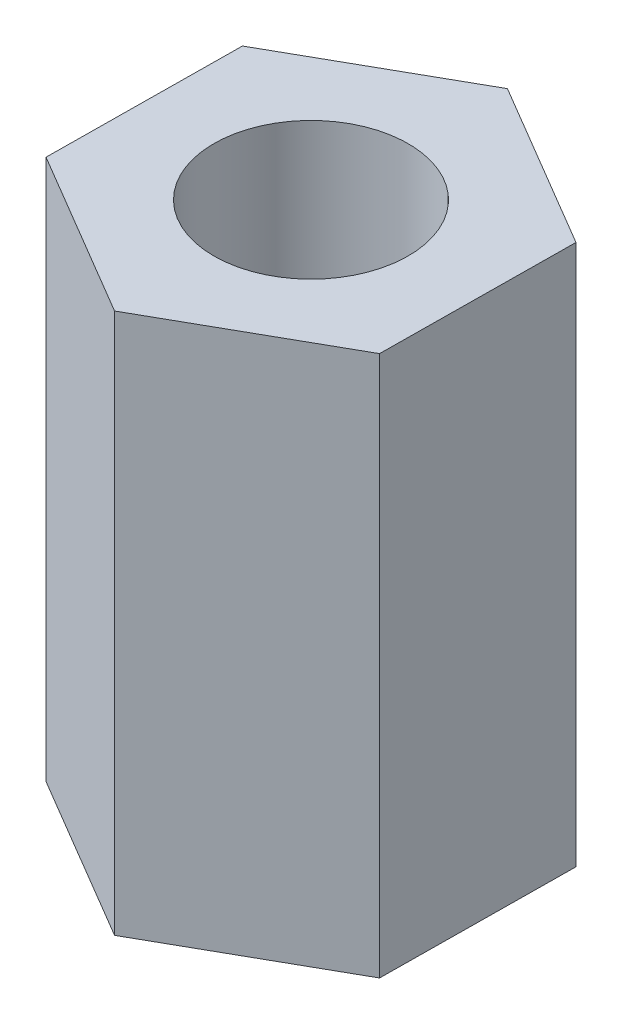
SolidWorks part; units mm, degrees
ref_plane "前视基准面" through (0, 0, 0) normal (0, 0, 1) x (1, 0, 0)
ref_plane "上视基准面" through (0, 0, 0) normal (0, 1, 0) x (1, 0, 0)
ref_plane "右视基准面" through (0, 0, 0) normal (1, 0, 0) x (0, 0, -1)
sketch "草图1" plane through (0, 0, 0) normal (0, 1, 0) x (1, 0, 0)
  line L1 (-2.583, 1.5257) -> (-2.6129, -1.4741)
  line L2 (-2.6129, -1.4741) -> (-0.0298, -2.9999)
  line L3 (-0.0298, -2.9999) -> (2.583, -1.5257)
  line L4 (2.583, -1.5257) -> (2.6129, 1.4741)
  line L5 (2.6129, 1.4741) -> (0.0298, 2.9999)
  line L6 (0.0298, 2.9999) -> (-2.583, 1.5257)
  circle A0 centre (0, 0) radius 1.5
  dimension "D2" = 3
  dimension "D1" = 6
extrude "凸台-拉伸1" add sketch "草图1" along normal blind 8.34
